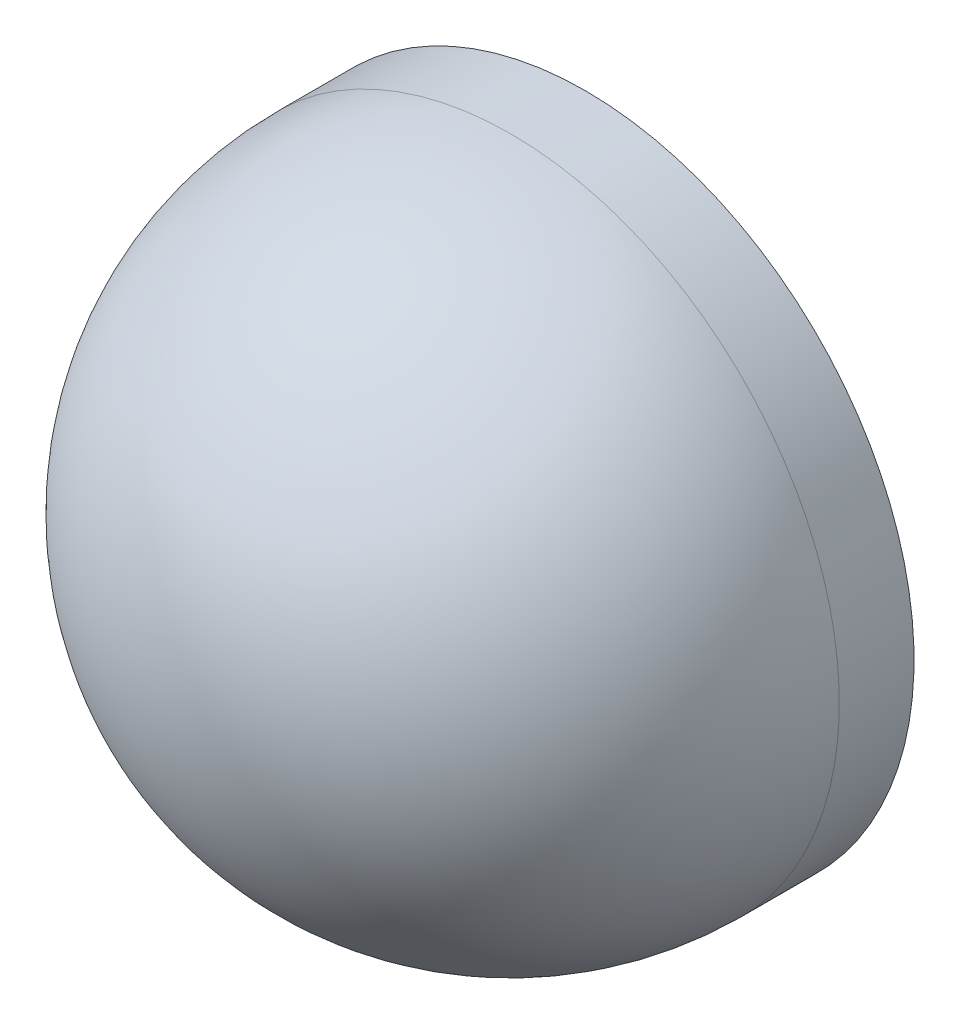
SolidWorks part; units mm, degrees
ref_plane "前视基准面" through (0, 0, 0) normal (0, 0, 1) x (1, 0, 0)
ref_plane "上视基准面" through (0, 0, 0) normal (0, 1, 0) x (1, 0, 0)
ref_plane "右视基准面" through (0, 0, 0) normal (1, 0, 0) x (0, 0, -1)
sketch "草图1" plane through (0, 0, 0) normal (0, 0, 1) x (1, 0, 0)
  line L0 (-11.7, 0) -> (-13.2, 0)
  line L1 (11.7, 0) -> (13.2, 0)
  circle A0 centre (0, 0) radius 11.7 construction
  circle A1 centre (0, 0) radius 13.2 construction
  arc A2 (-11.7, 0) -> (11.7, 0) centre (0, 0) cw
  arc A3 (-13.2, 0) -> (13.2, 0) centre (0, 0) cw
  point P10 (13.3824, 0)
  dimension "D1" = 23.4
revolve "旋转1" add sketch "草图1" angle 180 about L1
sketch "草图2" plane through (0, 0, 0) normal (0, 0, -1) x (-1, 0, 0)
  circle A2 centre (0, 0) radius 11.7
  circle A3 centre (0, 0) radius 13.2
extrude "凸台-拉伸1" add sketch "草图2" along normal blind 3
